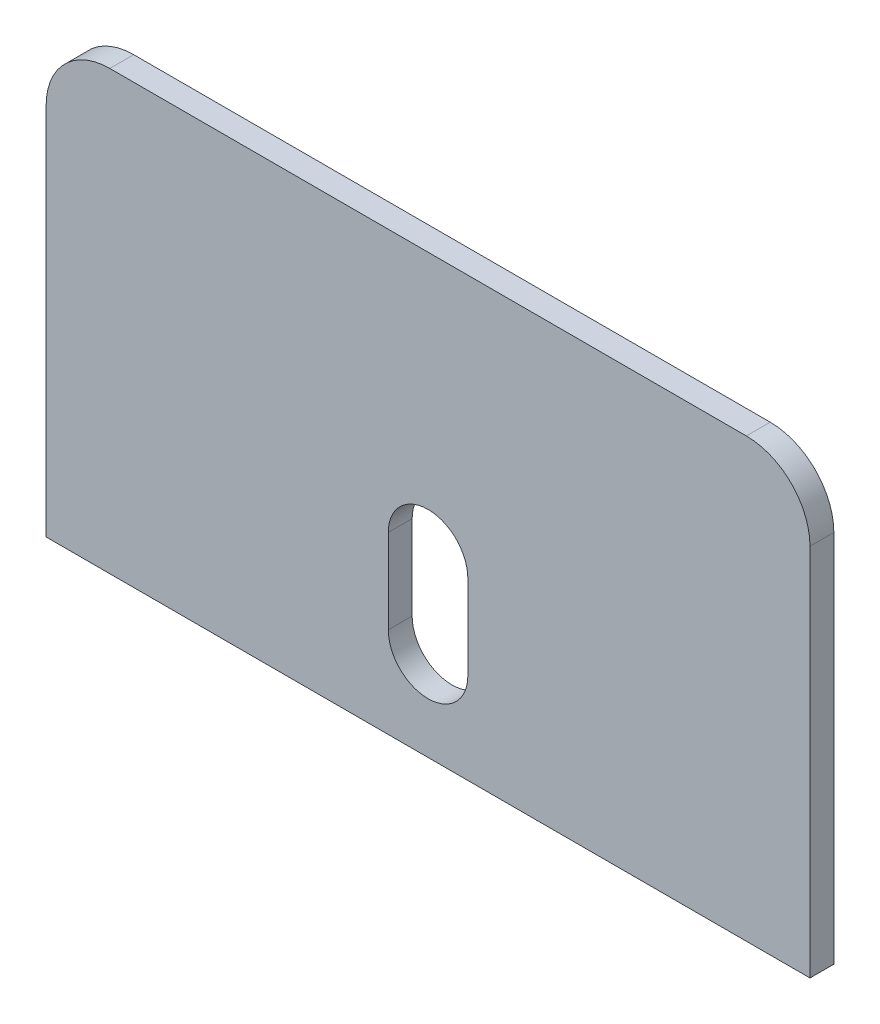
SolidWorks part; units mm, degrees
other "Camera1"
material "3.0517 (EN-AW 3003)"
ref_plane "Front Plane" through (0, 0, 0) normal (0, 0, 1) x (1, 0, 0)
ref_plane "Top Plane" through (0, 0, 0) normal (0, 1, 0) x (1, 0, 0)
ref_plane "Right Plane" through (0, 0, 0) normal (1, 0, 0) x (0, 0, -1)
sketch "Sketch1" plane through (0, 0, 0) normal (0, 0, 1) x (1, 0, 0)
  line L0 (0, -16.1) -> (0, -5.5) construction
  line L1 (48, -27.5) -> (-48, -27.5)
  line L2 (48, -27.5) -> (48, 27.5)
  line L3 (48, 27.5) -> (-48, 27.5)
  line L4 (-48, -27.5) -> (-48, 27.5)
  line L5 (48, -27.5) -> (-48, 27.5) construction
  line L6 (48, 27.5) -> (-48, -27.5) construction
  line L7 (-5, -16.1) -> (-5, -5.5)
  line L8 (5, -16.1) -> (5, -5.5)
  arc A0 (-5, -16.1) -> (5, -16.1) centre (0, -16.1) ccw
  arc A1 (5, -5.5) -> (-5, -5.5) centre (0, -5.5) ccw
  point P0 (0, 0)
  point P8 (0, -10.8)
  dimension "D4" = 5
  dimension "D1" = 55
  dimension "D2" = 96
  dimension "D3" = 10.6
  dimension "D5" = 11.4
extrude "Boss-Extrude1" add sketch "Sketch1" along normal mid plane 3
sketch "Sketch2" plane through (0, 0, -1.5) normal (0, 0, -1) x (-1, 0, 0)
  line L0 (-48, -14.5) -> (-54, -14.5)
  line L1 (-48, -27.5) -> (-48, 27.5) construction
  line L2 (-54, -14.5) -> (-54, -13.5)
  line L3 (-54, -13.5) -> (-48, -13.5)
  line L4 (48, -27.5) -> (-48, -27.5) construction
  line L8 (0, 27.5) -> (0, -27.5) construction
  line L9 (-48, 27.5) -> (48, 27.5) construction
  line L10 (48, 0) -> (-48, 0) construction
  line L11 (48, 27.5) -> (48, -27.5) construction
  line L15 (54, -13.5) -> (48, -13.5)
  line L16 (54, -14.5) -> (54, -13.5)
  line L17 (48, -14.5) -> (54, -14.5)
  line L18 (48, 14.5) -> (54, 14.5)
  line L19 (54, 14.5) -> (54, 13.5)
  line L20 (54, 13.5) -> (48, 13.5)
  line L27 (-54, 13.5) -> (-48, 13.5)
  line L28 (-54, 14.5) -> (-54, 13.5)
  line L29 (-48, 14.5) -> (-54, 14.5)
  line L30 (-48, -13.5) -> (-48, -14.5)
  line L33 (48, -14.5) -> (48, -13.5)
  line L34 (48, 13.5) -> (48, 14.5)
  line L37 (-48, 14.5) -> (-48, 13.5)
  dimension "D1" = 6
  dimension "D2" = 1
  dimension "D6" = 13
fillet "Fillet1" radius 8 2 edges at (48, 27.5, 0) (-48, 27.5, 0)
